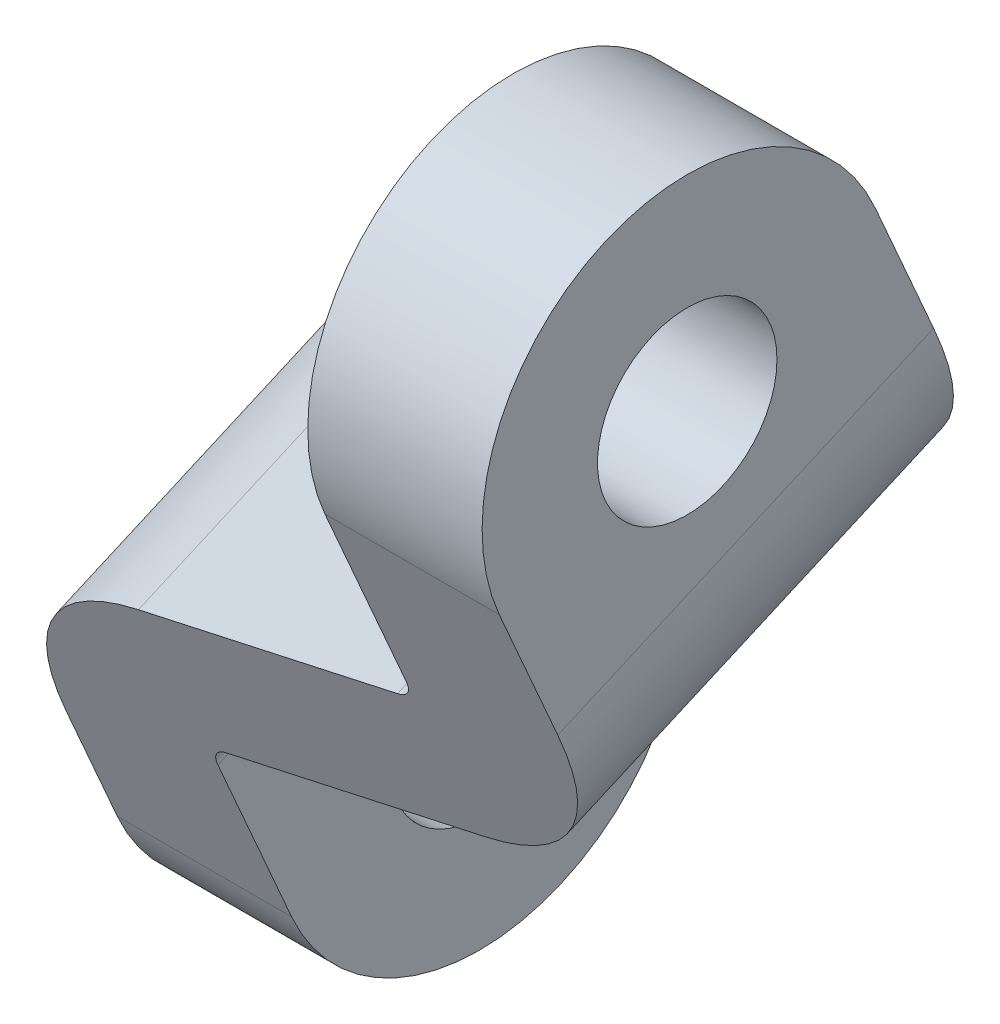
SolidWorks part; units mm, degrees
ref_plane "Front Plane" through (0, 0, 0) normal (0, 0, 1) x (1, 0, 0)
ref_plane "Top Plane" through (0, 0, 0) normal (0, 1, 0) x (1, 0, 0)
ref_plane "Right Plane" through (0, 0, 0) normal (1, 0, 0) x (0, 0, -1)
ref_plane "Plane1" through (-37.3464, 0, 0) normal (-1, 0, 0) x (0, -1, 0)
sketch "Sketch1" plane through (-37.3464, 0, 0) normal (-1, 0, 0) x (0, -1, 0)
  line L0 (51.1366, -50.1142) -> (63.8134, -55.6642)
  line L1 (67.0218, -48.3358) -> (54.345, -42.7858)
  arc A0 (63.8134, -55.6642) -> (67.0218, -48.3358) centre (65.4176, -52) ccw
  arc A1 (54.345, -42.7858) -> (51.1366, -50.1142) centre (52.7408, -46.45) ccw
extrude "Boss-Extrude1" add sketch "Sketch1" against normal blind 13
sketch "Sketch2" plane through (0, 6.9779, -15.9383) normal (0, -0.4011, 0.9161) x (1, 0, 0)
  line L0 (-37.3464, -62.5422) -> (-37.3464, -74.8056)
  line L1 (-37.3464, -74.8056) -> (-27.7464, -74.8056)
  line L2 (-27.7464, -74.8056) -> (-27.7464, -62.5422)
  line L3 (-27.7464, -62.5422) -> (-37.3464, -62.5422)
  line L4 (-24.3464, -80.7809) -> (-24.3464, -66.9424) construction
  line L5 (-37.3464, -80.7809) -> (-37.3464, -66.9424) construction
  dimension "D1" = 3.4
extrude "Cut-Extrude1" cut sketch "Sketch2" against normal through all
draft "Draft1" type of draft neutral plane draft angle 20 faces to draft 1 face at (-32.5464, -59.944, -49.6036) neutral plane through (-37.3464, -52.7408, -46.45) neutral plane normal (-1, 0, 0) parameters "D1"=20
sketch "Sketch3" plane through (0, 6.9779, -15.9383) normal (0, -0.4011, 0.9161) x (1, 0, 0)
  line L0 (-18.2703, -85.8691) -> (-18.2703, -71.0753)
  line L1 (-18.2703, -71.0753) -> (-33.9464, -76.7809)
  line L2 (-33.9464, -76.7809) -> (-33.9464, -85.8691)
  line L3 (-33.9464, -85.8691) -> (-18.2703, -85.8691)
  point P4 (-18.0504, -71.7204)
  dimension "D1" = 110
extrude "Cut-Extrude2" cut sketch "Sketch3" against normal through all
hole_wizard "Hole1" positions "Sketch5" profile "Sketch4" legacy end condition up to next
sketch "Sketch5" plane through (-37.3464, 0, 0) normal (-1, 0, 0) x (0, 0, 1)
  point P0 (-52, -65.4176)
sketch "Sketch4" plane through (-37.3464, -65.4176, -52) normal (0, 1, 0) x (0, 0, 1)
  line L0 (0, 0) -> (0, 3.4)
  line L1 (0, 3.4) -> (1.75, 3.4)
  line L2 (1.75, 3.4) -> (1.75, 0)
  line L3 (1.75, 0) -> (0, 0)
  line L4 (0, 110) -> (0, -10) construction
  dimension "Diameter" = 3.5
  dimension "Depth" = 3.4
hole_wizard "Hole2" positions "Sketch7" profile "Sketch6" legacy end condition up to next
sketch "Sketch7" plane through (-24.3464, 0, 0) normal (1, 0, 0) x (0, 0, -1)
  point P0 (46.45, -52.7408)
sketch "Sketch6" plane through (-24.3464, -52.7408, -46.45) normal (0, 1, 0) x (0, 0, -1)
  line L0 (0, 0) -> (0, 3.4)
  line L1 (0, 3.4) -> (1.75, 3.4)
  line L2 (1.75, 3.4) -> (1.75, 0)
  line L3 (1.75, 0) -> (0, 0)
  line L4 (0, 110) -> (0, -10) construction
  dimension "Diameter" = 3.5
  dimension "Depth" = 3.4
fillet "Fillet1" radius 0.6 2 edges at (-27.7464, -56.7432, -48.2023) (-33.9464, -61.7534, -50.3958)
fillet "Fillet2" radius 5 2 edges at (-37.3464, -59.944, -49.6036) (-24.3464, -58.5526, -48.9945)
